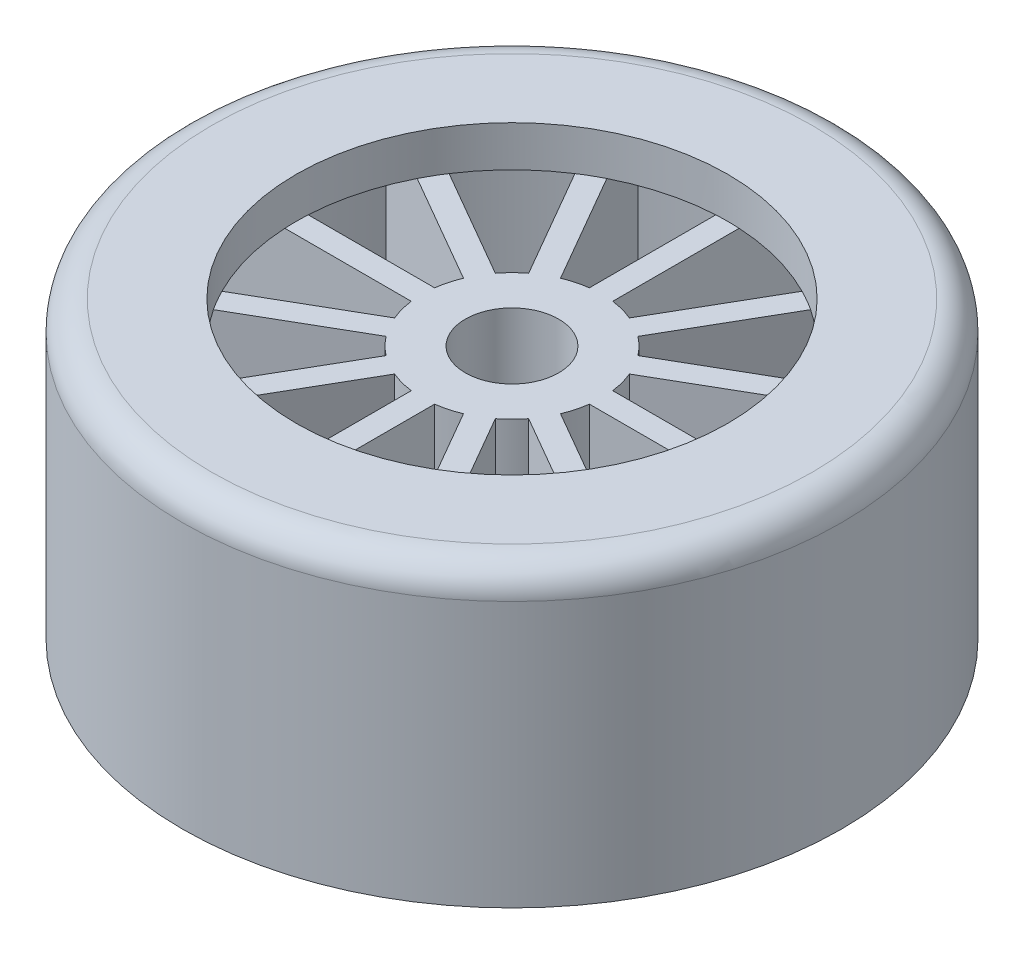
SolidWorks part; units mm, degrees
ref_plane "Plano frontal" through (0, 0, 0) normal (0, 0, 1) x (1, 0, 0)
ref_plane "Plano superior" through (0, 0, 0) normal (0, 1, 0) x (1, 0, 0)
ref_plane "Plano direito" through (0, 0, 0) normal (1, 0, 0) x (0, 0, -1)
sketch "Esboço1" plane through (0, 0, 0) normal (0, 1, 0) x (1, 0, 0)
  circle A0 centre (0, 0) radius 28.25
extrude "Ressalto-extrusão1" add sketch "Esboço1" along normal mid plane 25.25
sketch "Esboço2" plane through (0, 12.625, 0) normal (0, 1, 0) x (1, 0, 0)
  circle A0 centre (0, 0) radius 18.5
extrude "Corte-extrusão1" cut sketch "Esboço2" against normal blind 3.5
sketch "Esboço3" plane through (0, -12.625, 0) normal (0, -1, 0) x (1, 0, 0)
  circle A3 centre (0, 0) radius 25.75
extrude "Corte-extrusão2" cut sketch "Esboço3" against normal up to surface (21.75 mm away) up to face at (0, 9.125, 18.5)
sketch "Esboço4" plane through (0, 0, 0) normal (0, 1, 0) x (1, 0, 0)
  line L0 (4.6834, 6.1119) -> (13.741, 21.8002)
  line L1 (1, 7.6348) -> (1, 25.75)
  line L2 (-1, 7.6348) -> (-1, 25.75)
  line L3 (2.9514, 7.1119) -> (12.009, 22.8002)
  line L4 (7.1119, 2.9514) -> (22.8002, 12.009)
  line L5 (6.1119, 4.6834) -> (21.8002, 13.741)
  line L6 (7.6348, -1) -> (25.75, -1)
  line L7 (7.6348, 1) -> (25.75, 1)
  line L8 (6.1119, -4.6834) -> (21.8002, -13.741)
  line L9 (7.1119, -2.9514) -> (22.8002, -12.009)
  line L10 (2.9514, -7.1119) -> (12.009, -22.8002)
  line L11 (4.6834, -6.1119) -> (13.741, -21.8002)
  line L12 (-1, -7.6348) -> (-1, -25.75)
  line L13 (1, -7.6348) -> (1, -25.75)
  line L14 (-4.6834, -6.1119) -> (-13.741, -21.8002)
  line L15 (-2.9514, -7.1119) -> (-12.009, -22.8002)
  line L16 (-7.1119, -2.9514) -> (-22.8002, -12.009)
  line L17 (-6.1119, -4.6834) -> (-21.8002, -13.741)
  line L18 (-7.6348, 1) -> (-25.75, 1)
  line L19 (-7.6348, -1) -> (-25.75, -1)
  line L20 (-6.1119, 4.6834) -> (-21.8002, 13.741)
  line L21 (-7.1119, 2.9514) -> (-22.8002, 12.009)
  line L22 (-2.9514, 7.1119) -> (-12.009, 22.8002)
  line L23 (-4.6834, 6.1119) -> (-13.741, 21.8002)
  circle A1 centre (0, 0) radius 4
  arc A2 (13.741, 21.8002) -> (12.009, 22.8002) centre (0, 0) ccw
  arc A4 (1, 25.75) -> (-1, 25.75) centre (0, 0) ccw
  arc A5 (6.1119, 4.6834) -> (4.6834, 6.1119) centre (0, 0) ccw
  arc A6 (22.8002, 12.009) -> (21.8002, 13.741) centre (0, 0) ccw
  arc A7 (7.6348, 1) -> (7.1119, 2.9514) centre (0, 0) ccw
  arc A8 (25.75, -1) -> (25.75, 1) centre (0, 0) ccw
  arc A9 (7.1119, -2.9514) -> (7.6348, -1) centre (0, 0) ccw
  arc A10 (21.8002, -13.741) -> (22.8002, -12.009) centre (0, 0) ccw
  arc A11 (4.6834, -6.1119) -> (6.1119, -4.6834) centre (0, 0) ccw
  arc A12 (12.009, -22.8002) -> (13.741, -21.8002) centre (0, 0) ccw
  arc A13 (1, -7.6348) -> (2.9514, -7.1119) centre (0, 0) ccw
  arc A14 (-1, -25.75) -> (1, -25.75) centre (0, 0) ccw
  arc A15 (2.9514, 7.1119) -> (1, 7.6348) centre (0, 0) ccw
  arc A16 (-2.9514, -7.1119) -> (-1, -7.6348) centre (0, 0) ccw
  arc A17 (-13.741, -21.8002) -> (-12.009, -22.8002) centre (0, 0) ccw
  arc A18 (-6.1119, -4.6834) -> (-4.6834, -6.1119) centre (0, 0) ccw
  arc A19 (-22.8002, -12.009) -> (-21.8002, -13.741) centre (0, 0) ccw
  arc A20 (-7.6348, -1) -> (-7.1119, -2.9514) centre (0, 0) ccw
  arc A21 (-25.75, 1) -> (-25.75, -1) centre (0, 0) ccw
  arc A22 (-7.1119, 2.9514) -> (-7.6348, 1) centre (0, 0) ccw
  arc A23 (-21.8002, 13.741) -> (-22.8002, 12.009) centre (0, 0) ccw
  arc A24 (-4.6834, 6.1119) -> (-6.1119, 4.6834) centre (0, 0) ccw
  arc A25 (-12.009, 22.8002) -> (-13.741, 21.8002) centre (0, 0) ccw
  arc A26 (-1, 7.6348) -> (-2.9514, 7.1119) centre (0, 0) ccw
  point P51 (0, 0)
  point P66 (0, 0)
  dimension "D1" = 12
extrude "Ressalto-extrusão2" add sketch "Esboço4" along normal up to surface (9.125 mm away) and the other way blind 7.625 up to face at (0, 9.125, 18.5)
fillet "Filete1" radius 2.5 1 edges at (0, 12.625, 28.25)
